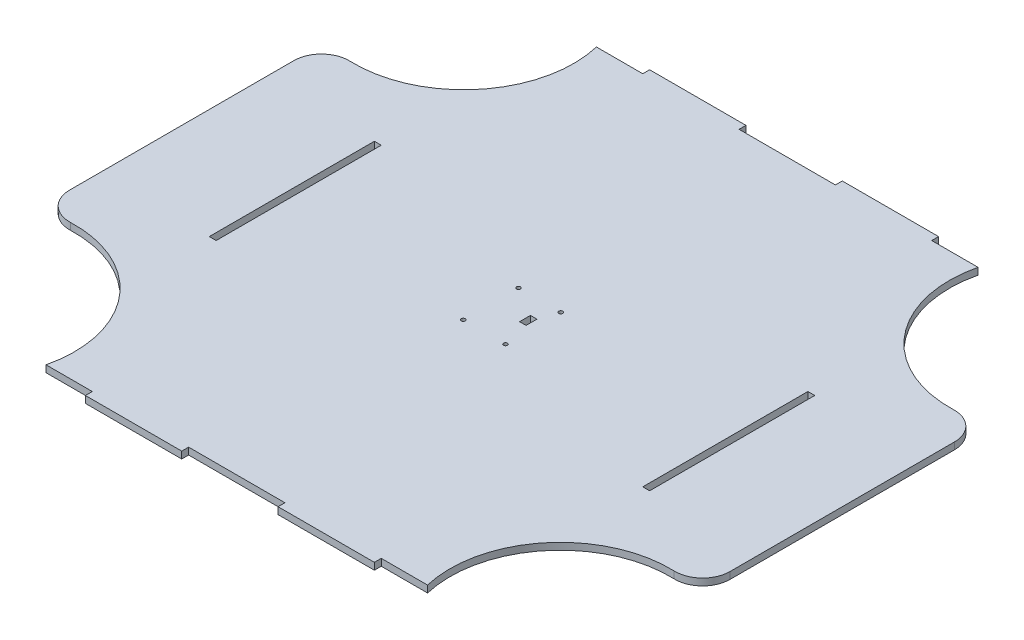
SolidWorks part; units mm, degrees
ref_plane "Front Plane" through (0, 0, 0) normal (0, 0, 1) x (1, 0, 0)
ref_plane "Top Plane" through (0, 0, 0) normal (0, 1, 0) x (1, 0, 0)
ref_plane "Right Plane" through (0, 0, 0) normal (1, 0, 0) x (0, 0, -1)
sketch "Sketch1" plane through (0, 0, 0) normal (0, 1, 0) x (1, 0, 0)
  line L1 (-304.8, -260.35) -> (304.8, -260.35)
  line L2 (-304.8, -260.35) -> (-304.8, 260.35)
  line L3 (-304.8, 260.35) -> (304.8, 260.35)
  line L4 (304.8, -260.35) -> (304.8, 260.35)
  line L5 (-304.8, -260.35) -> (304.8, 260.35) construction
  line L6 (-304.8, 260.35) -> (304.8, -260.35) construction
  line L8 (0, -3.4925) -> (0, 3.4925) construction
  line L11 (-3.4925, 0) -> (3.4925, 0) construction
  arc A0 (-177.8, 260.35) -> (-304.8, 133.35) centre (-274.901, 230.451) cw
  arc A1 (177.8, 260.35) -> (304.8, 133.35) centre (274.901, 230.451) ccw
  arc A2 (177.8, -260.35) -> (304.8, -133.35) centre (274.901, -230.451) cw
  arc A3 (-177.8, -260.35) -> (-304.8, -133.35) centre (-274.901, -230.451) ccw
  point P0 (0, 0)
  dimension "D3" = 101.6
  dimension "D1" = 609.6
  dimension "D2" = 520.7
  dimension "D4" = 127
  dimension "D5" = 127
extrude "Boss-Extrude1" add sketch "Sketch1" along normal blind 6.35
sketch "Sketch4" plane through (0, 6.35, 0) normal (0, 1, 0) x (1, 0, 0)
  line L60 (-177.8, 260.35) -> (177.8, 260.35) construction
  line L61 (-222.25, 260.35) -> (-133.35, 260.35)
  line L62 (-222.25, 260.35) -> (-222.25, 254)
  line L63 (-222.25, 254) -> (-133.35, 254)
  line L64 (-133.35, 260.35) -> (-133.35, 254)
  line L65 (-44.45, 260.35) -> (44.45, 260.35)
  line L66 (-44.45, 260.35) -> (-44.45, 254)
  line L67 (-44.45, 254) -> (44.45, 254)
  line L68 (44.45, 260.35) -> (44.45, 254)
  line L69 (133.35, 260.35) -> (222.25, 260.35)
  line L70 (133.35, 260.35) -> (133.35, 254)
  line L71 (133.35, 254) -> (222.25, 254)
  line L72 (222.25, 260.35) -> (222.25, 254)
  point P4 (-177.8, 260.35)
  point P12 (0, 254)
  point P17 (177.8, 260.35)
  dimension "D1" = 6.35
  dimension "D2" = 88.9
  dimension "D4" = 88.9
  dimension "D3" = 6.35
  dimension "D5" = 6.35
  dimension "D6" = 88.9
extrude "Cut-Extrude2" cut sketch "Sketch4" against normal through all
mirror "Mirror2" about plane through (0, 0, 0) normal (0, 0, 1) of "Cut-Extrude2"
fillet "Fillet2" radius 25.4 4 edges at (304.8, 3.175, 133.35) (304.8, 3.175, -133.35) (-304.8, 3.175, -133.35) (-304.8, 3.175, 133.35)
sketch "Sketch6" plane through (0, 6.35, 0) normal (0, 1, 0) x (1, 0, 0)
  line L1 (-203.2, 76.2) -> (-196.85, 76.2)
  line L2 (-203.2, 76.2) -> (-203.2, -76.2)
  line L3 (-203.2, -76.2) -> (-196.85, -76.2)
  line L4 (-196.85, 76.2) -> (-196.85, -76.2)
  line L6 (196.85, 76.2) -> (203.2, 76.2)
  line L7 (196.85, 76.2) -> (196.85, -76.2)
  line L8 (196.85, -76.2) -> (203.2, -76.2)
  line L9 (203.2, 76.2) -> (203.2, -76.2)
  point P6 (-196.85, 0)
  dimension "D1" = 152.4
  dimension "D2" = 6.35
  dimension "D3" = 196.85
  dimension "D4" = 196.85
extrude "Cut-Extrude3" cut sketch "Sketch6" against normal through all
sketch "Sketch7" plane through (0, 6.35, 0) normal (0, 1, 0) x (1, 0, 0)
  line L0 (0, -3.4925) -> (0, 3.4925) construction
  line L1 (-28.5, 28.5) -> (28.5, 28.5)
  line L2 (-28.5, 28.5) -> (-28.5, -28.5)
  line L3 (-28.5, -28.5) -> (28.5, -28.5)
  line L4 (28.5, 28.5) -> (28.5, -28.5)
  line L5 (-28.5, 28.5) -> (28.5, -28.5) construction
  line L6 (-28.5, -28.5) -> (28.5, 28.5) construction
  line L7 (-3.4925, 0) -> (3.4925, 0) construction
  line L9 (8, 9) -> (14, 9)
  line L10 (8, 9) -> (8, -1)
  line L11 (8, -1) -> (14, -1)
  line L12 (14, 9) -> (14, -1)
  line L13 (8, 9) -> (14, -1) construction
  line L14 (8, -1) -> (14, 9) construction
  circle A0 centre (-19.5, 25.5) radius 1.8
  circle A1 centre (19.5, 25.5) radius 1.8
  circle A2 centre (-19.5, -25.5) radius 1.8
  circle A3 centre (19.5, -25.5) radius 1.8
  point P0 (0, 0)
  point P18 (11, 4)
  dimension "D2" = 3.6
  dimension "D1" = 57
  dimension "D3" = 3
  dimension "D4" = 9
  dimension "D5" = 10
  dimension "D6" = 6
  dimension "D7" = 14.5
  dimension "D8" = 19.5
extrude "Cut-Extrude4" cut sketch "Sketch7" against normal through all contours L12 L9 L10 L11 | A0 | A2 | A3 | A1
